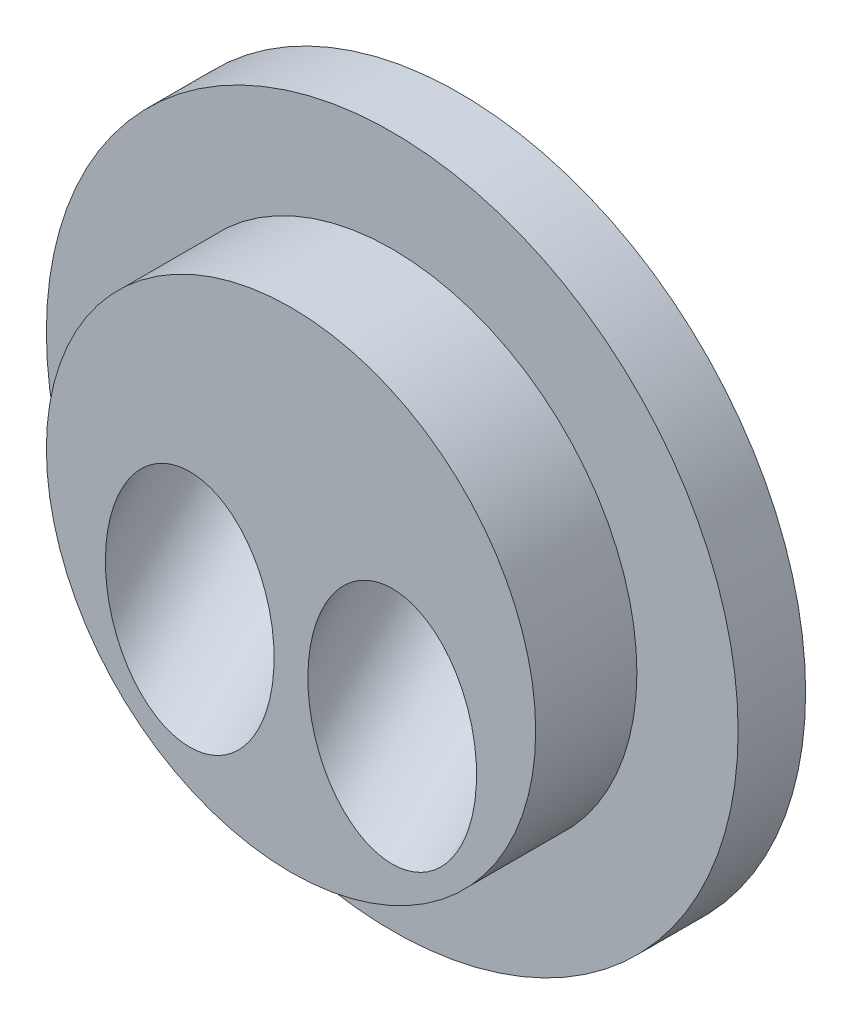
SolidWorks part; units mm, degrees
ref_plane "Přední rovina" through (0, 0, 0) normal (0, 0, 1) x (1, 0, 0)
ref_plane "Horní rovina" through (0, 0, 0) normal (0, 1, 0) x (1, 0, 0)
ref_plane "Pravá rovina" through (0, 0, 0) normal (1, 0, 0) x (0, 0, -1)
sketch "Outer sketch" plane through (0, 0, 0) normal (0, 0, 1) x (1, 0, 0)
  circle A0 centre (0, 0) radius 10.25
  dimension "D1" = 20.5
extrude "Outer" add sketch "Outer sketch" along normal blind 2
sketch "Inner sketch" plane through (0, 0, 2) normal (0, 0, 1) x (1, 0, 0)
  circle A0 centre (0, 0) radius 7.25
  dimension "D1" = 14.5
extrude "Inner" add sketch "Inner sketch" along normal blind 3
sketch "Plane 1" plane through (0, 0, 5) normal (0, 0, 1) x (1, 0, 0)
  line L0 (0, 0) -> (0, 2.5)
  line L1 (0, 2.5) -> (4.9729, 2.5)
  circle A0 centre (-3, -2) radius 2.5
  circle A1 centre (3, -2) radius 2.5
  dimension "D2" = 5
  dimension "D1" = 2.5
  dimension "D3" = 2
  dimension "D4" = 3
  dimension "D5" = 4.9729
sketch "Plane 2" plane through (0, 0, 0) normal (0, 0, -1) x (-1, 0, 0)
  line L0 (0, 0) -> (0, -2.5)
  dimension "D1" = 2.5
ref_plane "Rovina2" through (0, -1.25, 1.25) normal (0, 0.7071, -0.7071) x (-1, 0, 0)
sketch "Skica8" plane through (0, -0.0421, 2.4579) normal (0, -0.7071, 0.7071) x (1, 0, 0)
  circle A0 centre (-3, 0.4131) radius 2.5
  circle A1 centre (3, 0.4131) radius 2.5
  dimension "D1" = 5
  dimension "D2" = 5
extrude "Odebrat vysunutím2" cut sketch "Skica8" against normal through all and the other way through all
